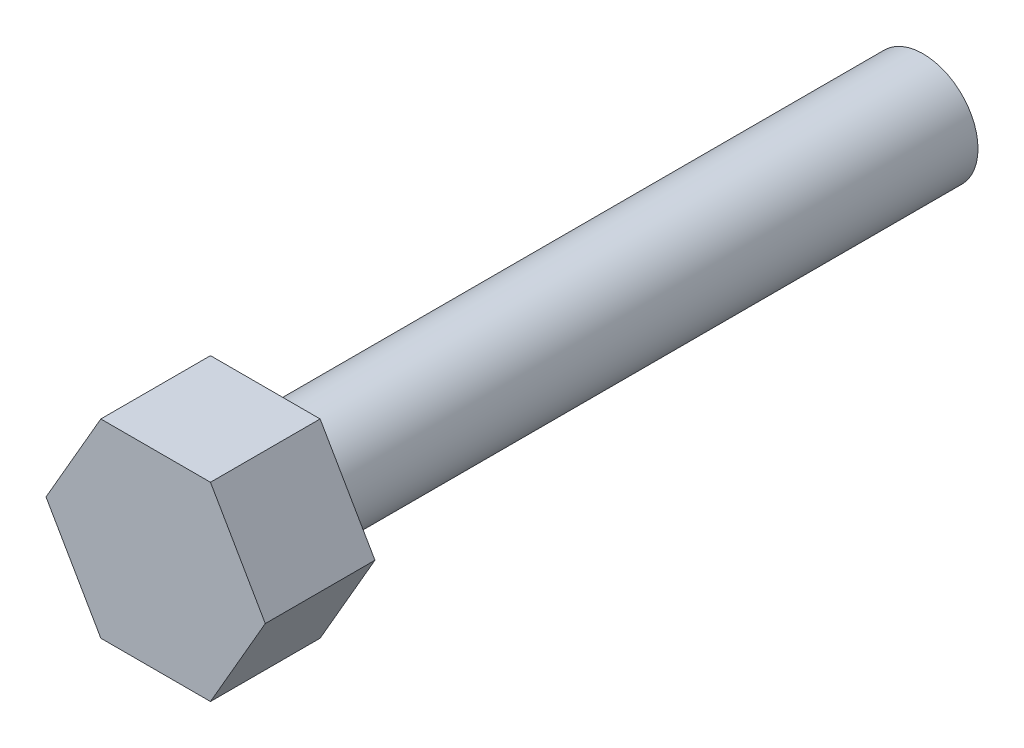
SolidWorks part; units mm, degrees
ref_plane "Ön Düzlem" through (0, 0, 0) normal (0, 0, 1) x (1, 0, 0)
ref_plane "Üst Düzlem" through (0, 0, 0) normal (0, 1, 0) x (1, 0, 0)
ref_plane "Sağ Düzlem" through (0, 0, 0) normal (1, 0, 0) x (0, 0, -1)
sketch "Çizim1" plane through (0, 0, 0) normal (0, 0, 1) x (1, 0, 0)
  circle A0 centre (0, 0) radius 2.5
  dimension "D1" = 5
extrude "Yükseklik-Ekstrüzyon1" add sketch "Çizim1" along normal blind 30
sketch "Çizim2" plane through (0, 0, 30) normal (0, 0, 1) x (1, 0, 0)
  line L1 (5, 0) -> (2.5, 4.3301)
  line L2 (2.5, 4.3301) -> (-2.5, 4.3301)
  line L3 (-2.5, 4.3301) -> (-5, 0)
  line L4 (-5, 0) -> (-2.5, -4.3301)
  line L5 (-2.5, -4.3301) -> (2.5, -4.3301)
  line L6 (2.5, -4.3301) -> (5, 0)
  circle A0 centre (0, 0) radius 4.3301 construction
  dimension "D1" = 5
extrude "Yükseklik-Ekstrüzyon2" add sketch "Çizim2" along normal blind 5
